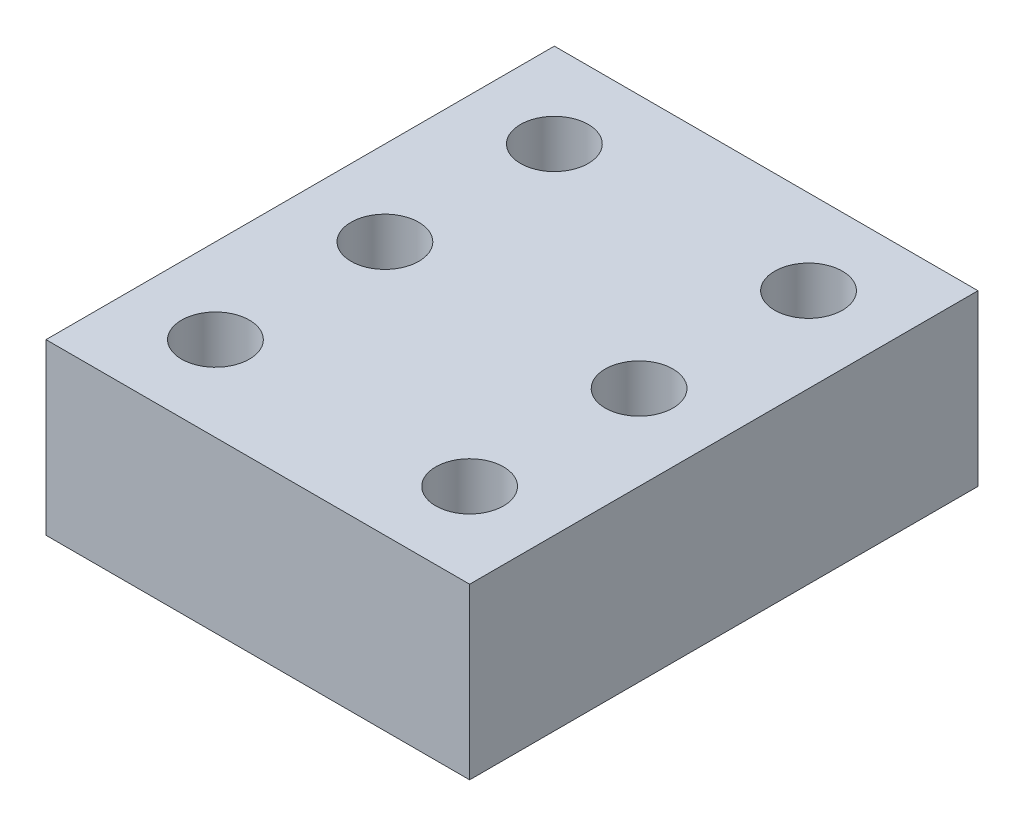
SolidWorks part; units mm, degrees
material "Acrylic (Medium-high impact)"
ref_plane "Front Plane" through (0, 0, 0) normal (0, 0, 1) x (1, 0, 0)
ref_plane "Top Plane" through (0, 0, 0) normal (0, 1, 0) x (1, 0, 0)
ref_plane "Right Plane" through (0, 0, 0) normal (1, 0, 0) x (0, 0, -1)
sketch "Sketch1" plane through (0, 0, 0) normal (0, 1, 0) x (1, 0, 0)
  line L5 (-12.5, 15) -> (12.5, 15)
  line L6 (-12.5, 15) -> (-12.5, -15)
  line L7 (-12.5, -15) -> (12.5, -15)
  line L8 (12.5, 15) -> (12.5, -15)
  circle A1 centre (7.5, 0) radius 2
  circle A2 centre (7.5, -10) radius 2
  circle A3 centre (-7.5, -10) radius 2
  circle A4 centre (-7.5, 0) radius 2
  circle A5 centre (-7.5, 10) radius 2
  circle A6 centre (7.5, 10) radius 2
  dimension "D5" = 10
  dimension "D6" = 4
  dimension "D7" = 4
  dimension "D8" = 4
  dimension "D9" = 4
  dimension "D10" = 10
  dimension "D1" = 30
  dimension "D2" = 25
  dimension "D3" = 15
  dimension "D4" = 12.5
  dimension "D11" = 5
  dimension "D12" = 5
  dimension "D13" = 5
  dimension "D14" = 5
  dimension "D15" = 5
  dimension "D16" = 5
  dimension "D17" = 5
  dimension "D18" = 10
  dimension "D20" = 5
  dimension "D21" = 10
extrude "Boss-Extrude1" add sketch "Sketch1" along normal blind 10
